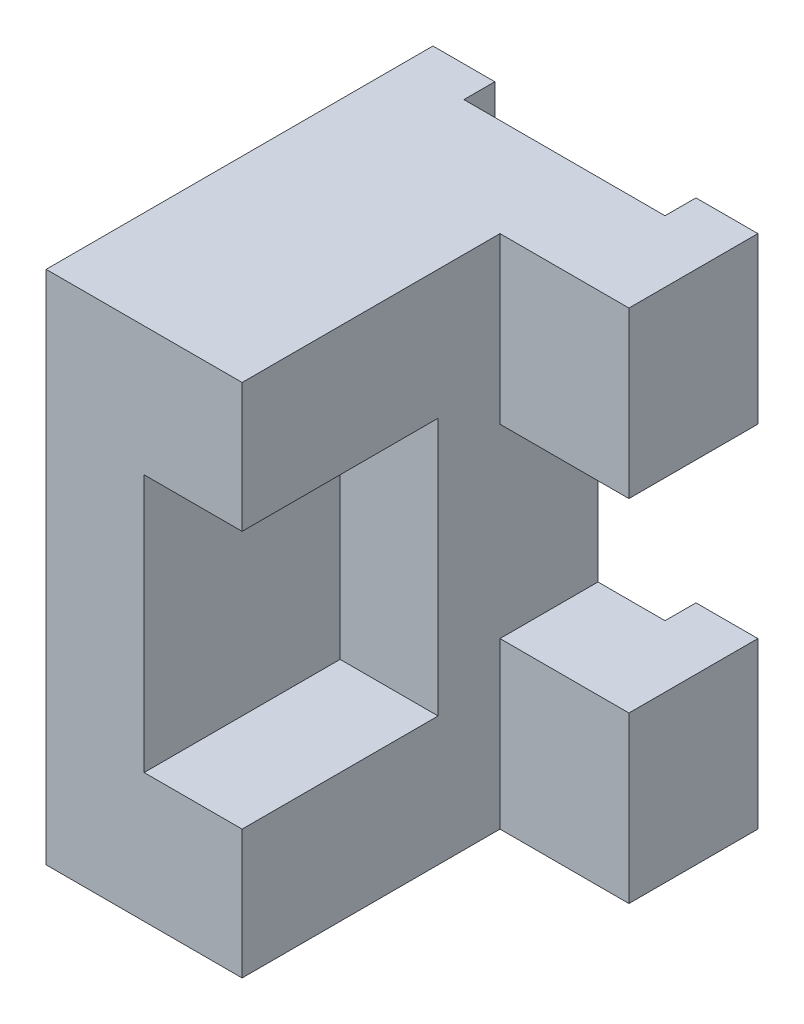
SolidWorks part; units mm, degrees
ref_plane "Front Plane" through (0, 0, 0) normal (1, 0, 0) x (0, 1, 0)
ref_plane "Top Plane" through (0, 0, 0) normal (0, 0, 1) x (0, 1, 0)
ref_plane "Right Plane" through (0, 0, 0) normal (0, 1, 0) x (-1, 0, 0)
sketch "Sketch1" plane through (0, 0, 0) normal (0, 1, 0) x (-1, 0, 0)
  line L0 (0, 0) -> (50000, 0) construction
  line L1 (0, 0) -> (0, 50000) construction
  line L2 (0, 0) -> (12, 0)
  line L3 (12, 0) -> (12, 6)
  line L4 (12, 6) -> (51, 6)
  line L5 (51, 6) -> (51, 0)
  line L6 (51, 0) -> (63, 0)
  line L7 (63, 0) -> (63, 75)
  line L8 (63, 75) -> (25, 75)
  line L9 (25, 75) -> (25, 25)
  line L10 (25, 25) -> (0, 25)
  line L11 (0, 25) -> (0, 0)
  dimension "D1" = 75
  dimension "D2" = 63
  dimension "D3" = 12
  dimension "D4" = 12
  dimension "D5" = 6
  dimension "D6" = 38
  dimension "D7" = 50
extrude "Boss-Extrude1" add sketch "Sketch1" along normal mid plane 100
sketch "Sketch2" plane through (0, 0, 75) normal (0, 0, 1) x (1, 0, 0)
  line L0 (-25, 25) -> (-44, 25)
  line L1 (-25, 50) -> (-25, -50) construction
  line L2 (-44, 25) -> (-44, -25)
  line L3 (-44, -25) -> (-25, -25)
  line L4 (-25, 50) -> (-25, -50) construction
  line L5 (-25, -25) -> (-25, 25)
  point P5 (-44, 0)
  dimension "D1" = 50
  dimension "D2" = 19
extrude "Cut-Extrude1" cut sketch "Sketch2" against normal blind 38
sketch "Sketch3" plane through (0, 0, 25) normal (0, 0, 1) x (1, 0, 0)
  line L0 (0, 50) -> (0, -50) construction
  line L1 (0, 18) -> (-25, 18)
  line L2 (0, 18) -> (0, -18)
  line L3 (0, -18) -> (-25, -18)
  line L4 (-25, 18) -> (-25, -18)
  line L5 (-25, 50) -> (-25, -50) construction
  line L6 (-25, -50) -> (0, -50) construction
  point P8 (-25, 0)
  dimension "D1" = 32
extrude "Cut-Extrude2" cut sketch "Sketch3" against normal blind 38
